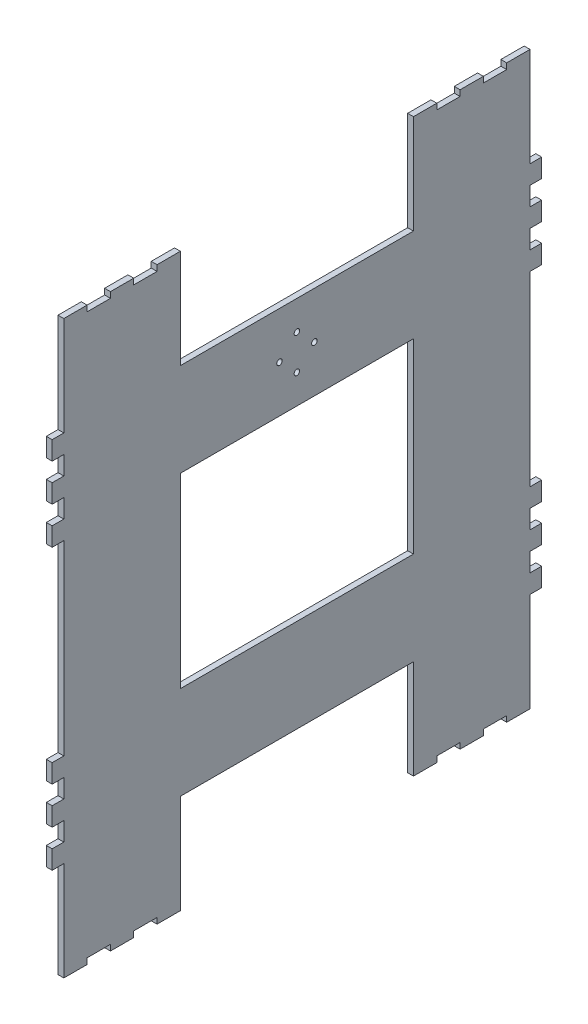
SolidWorks part; units mm, degrees
ref_plane "Front Plane" through (0, 0, 0) normal (0, 0, 1) x (1, 0, 0)
ref_plane "Top Plane" through (0, 0, 0) normal (0, 1, 0) x (1, 0, 0)
ref_plane "Right Plane" through (0, 0, 0) normal (1, 0, 0) x (0, 0, -1)
sketch "Sketch1" plane through (0, 0, 0) normal (1, 0, 0) x (0, 0, -1)
  line L0 (55, 0) -> (-55, 0) construction
  line L1 (-133.35, -155.575) -> (133.35, -155.575)
  line L2 (-133.35, -155.575) -> (-133.35, 155.575)
  line L3 (-133.35, 155.575) -> (133.35, 155.575)
  line L4 (133.35, -155.575) -> (133.35, 155.575)
  line L5 (-133.35, -155.575) -> (133.35, 155.575) construction
  line L6 (-133.35, 155.575) -> (133.35, -155.575) construction
  line L7 (-63.5, 155.575) -> (63.5, 155.575)
  line L8 (-63.5, 155.575) -> (-63.5, 101.6)
  line L9 (-63.5, 101.6) -> (63.5, 101.6)
  line L10 (63.5, 155.575) -> (63.5, 101.6)
  line L11 (-63.5, -155.575) -> (63.5, -155.575)
  line L12 (-63.5, -155.575) -> (-63.5, -101.6)
  line L13 (-63.5, -101.6) -> (63.5, -101.6)
  line L14 (63.5, -155.575) -> (63.5, -101.6)
  line L15 (-63.5, 50.8) -> (63.5, 50.8)
  line L16 (-63.5, 50.8) -> (-63.5, -50.8)
  line L17 (-63.5, -50.8) -> (63.5, -50.8)
  line L18 (63.5, 50.8) -> (63.5, -50.8)
  line L19 (76.2, 155.575) -> (88.9, 155.575)
  line L20 (76.2, 155.575) -> (76.2, 152.4)
  line L21 (76.2, 152.4) -> (88.9, 152.4)
  line L22 (88.9, 155.575) -> (88.9, 152.4)
  line L23 (101.6, 155.575) -> (114.3, 155.575)
  line L24 (101.6, 155.575) -> (101.6, 152.4)
  line L25 (101.6, 152.4) -> (114.3, 152.4)
  line L26 (114.3, 155.575) -> (114.3, 152.4)
  line L27 (101.6, -152.4) -> (114.3, -152.4)
  line L28 (114.3, -155.575) -> (114.3, -152.4)
  line L29 (101.6, -155.575) -> (114.3, -155.575)
  line L30 (101.6, -155.575) -> (101.6, -152.4)
  line L31 (76.2, -152.4) -> (88.9, -152.4)
  line L32 (88.9, -155.575) -> (88.9, -152.4)
  line L33 (76.2, -155.575) -> (88.9, -155.575)
  line L34 (76.2, -155.575) -> (76.2, -152.4)
  line L35 (0, 55) -> (0, -55) construction
  line L36 (-101.6, -155.575) -> (-101.6, -152.4)
  line L37 (-101.6, -155.575) -> (-114.3, -155.575)
  line L38 (-114.3, -155.575) -> (-114.3, -152.4)
  line L39 (-101.6, -152.4) -> (-114.3, -152.4)
  line L40 (-76.2, -155.575) -> (-76.2, -152.4)
  line L41 (-76.2, -155.575) -> (-88.9, -155.575)
  line L42 (-88.9, -155.575) -> (-88.9, -152.4)
  line L43 (-76.2, -152.4) -> (-88.9, -152.4)
  line L44 (-101.6, 152.4) -> (-114.3, 152.4)
  line L45 (-114.3, 155.575) -> (-114.3, 152.4)
  line L46 (-101.6, 155.575) -> (-114.3, 155.575)
  line L47 (-101.6, 155.575) -> (-101.6, 152.4)
  line L48 (-76.2, 152.4) -> (-88.9, 152.4)
  line L49 (-88.9, 155.575) -> (-88.9, 152.4)
  line L50 (-76.2, 155.575) -> (-88.9, 155.575)
  line L51 (-76.2, 155.575) -> (-76.2, 152.4)
  line L52 (-133.35, -101.6) -> (-127, -101.6)
  line L53 (133.35, 155.575) -> (127, 155.575)
  line L54 (133.35, 155.575) -> (133.35, 101.6)
  line L55 (133.35, 101.6) -> (127, 101.6)
  line L56 (127, 155.575) -> (127, 101.6)
  line L57 (133.35, 50.8) -> (127, 50.8)
  line L58 (133.35, 50.8) -> (133.35, -50.8)
  line L59 (133.35, -50.8) -> (127, -50.8)
  line L60 (127, 50.8) -> (127, -50.8)
  line L61 (133.35, -155.575) -> (127, -155.575)
  line L62 (133.35, -155.575) -> (133.35, -101.6)
  line L63 (133.35, -101.6) -> (127, -101.6)
  line L64 (127, -155.575) -> (127, -101.6)
  line L65 (-127, -155.575) -> (-127, -101.6)
  line L66 (-133.35, -155.575) -> (-127, -155.575)
  line L67 (-133.35, -155.575) -> (-133.35, -101.6)
  line L68 (-133.35, -50.8) -> (-127, -50.8)
  line L69 (-127, 50.8) -> (-127, -50.8)
  line L70 (-133.35, 50.8) -> (-127, 50.8)
  line L71 (-133.35, 50.8) -> (-133.35, -50.8)
  line L72 (-133.35, 101.6) -> (-127, 101.6)
  line L73 (-127, 155.575) -> (-127, 101.6)
  line L74 (-133.35, 155.575) -> (-127, 155.575)
  line L75 (-133.35, 155.575) -> (-133.35, 101.6)
  point P0 (0, 0)
  dimension "D1" = 311.15
  dimension "D2" = 266.7
  dimension "D3" = 53.975
  dimension "D4" = 127
  dimension "D5" = 12.7
  dimension "D6" = 127
  dimension "D7" = 6.35
  dimension "D8" = 53.975
  dimension "D9" = 50.8
  dimension "D10" = 50.8
  dimension "D11" = 53.975
  dimension "D12" = 101.6
  dimension "D13" = 12.7
  dimension "D14" = 12.7
  dimension "D15" = 12.7
  dimension "D16" = 12.7
  dimension "D17" = 3.175
  dimension "D18" = 53.975
  dimension "D19" = 50.8
extrude "Boss-Extrude1" add sketch "Sketch1" along normal blind 3.175 contours L14 L1 L4 L3 L10 L9 L8 L2 L12 L13 L15 L18 L17 L16
sketch "Sketch3" plane through (3.175, 0, 0) normal (1, 0, 0) x (0, 0, -1)
  line L0 (0, 85.7) -> (-9.5, 76.2)
  line L1 (-9.5, 76.2) -> (0, 66.7)
  line L2 (0, 66.7) -> (9.5, 76.2)
  line L3 (9.5, 76.2) -> (0, 85.7)
  line L5 (-63.5, 101.6) -> (63.5, 101.6) construction
  circle A0 centre (0, 85.7) radius 1.5
  circle A1 centre (9.5, 76.2) radius 1.5
  circle A2 centre (0, 66.7) radius 1.5
  circle A3 centre (-9.5, 76.2) radius 1.5
  point P11 (0, 0)
  point P12 (0, 0)
  dimension "D2" = 3
  dimension "D1" = 19
  dimension "D3" = 25.4
extrude "Cut-Extrude3" cut sketch "Sketch3" against normal blind 3.175 contours L3 A0 L0 | L1 A2 L2 | L2 A1 L3 | L0 A3 L1 | L1 A3 L0 | L2 A2 L1 | L3 A1 L2 | L0 A0 L3
sketch "Sketch4" plane through (3.175, 0, 0) normal (1, 0, 0) x (0, 0, -1)
  line L0 (133.35, 50.8) -> (133.35, 101.6) construction
  line L1 (133.35, 91.44) -> (127, 91.44)
  line L2 (133.35, 91.44) -> (133.35, 81.28)
  line L3 (133.35, 81.28) -> (127, 81.28)
  line L4 (127, 91.44) -> (127, 81.28)
  line L5 (127, 50.8) -> (127, -50.8) construction
  line L6 (133.35, 71.12) -> (127, 71.12)
  line L7 (133.35, 71.12) -> (133.35, 60.96)
  line L8 (133.35, 60.96) -> (127, 60.96)
  line L9 (127, 71.12) -> (127, 60.96)
  line L10 (133.35, 101.6) -> (127, 101.6) construction
  dimension "D1" = 10.16
  dimension "D2" = 10.16
  dimension "D3" = 10.16
extrude "Cut-Extrude4" cut sketch "Sketch4" against normal blind 3.175
mirror "Mirror3" about plane through (0, 0, 0) normal (0, 1, 0) of "Cut-Extrude4"
mirror "Mirror4" about plane through (0, 0, 0) normal (0, 0, 1) of "Cut-Extrude4", "Mirror3"
